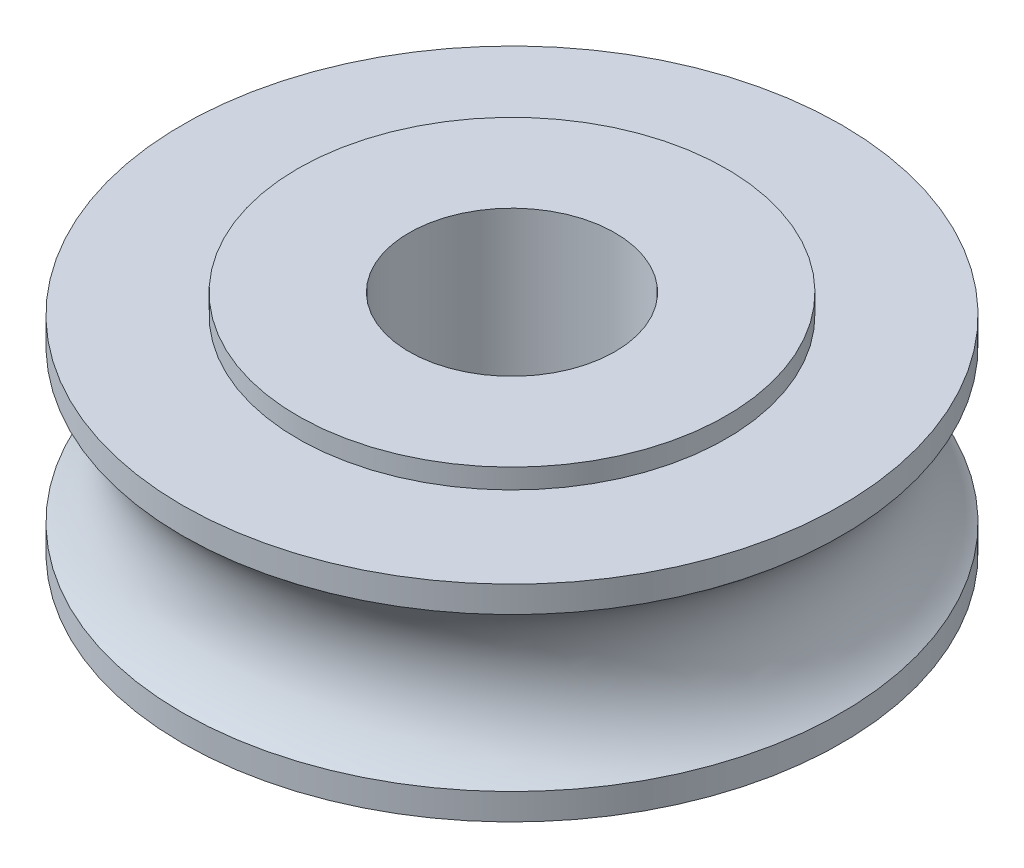
SolidWorks part; units mm, degrees
material "AISI 316 Annealed Stainless Steel Bar (SS)"
ref_plane "Front Plane" through (0, 0, 0) normal (0, 0, 1) x (1, 0, 0)
ref_plane "Top Plane" through (0, 0, 0) normal (0, 1, 0) x (1, 0, 0)
ref_plane "Right Plane" through (0, 0, 0) normal (1, 0, 0) x (0, 0, -1)
sketch "Sketch1" plane through (0, 0, 0) normal (0, 1, 0) x (1, 0, 0)
  circle A0 centre (0, 0) radius 12.7
extrude "Boss-Extrude1" add sketch "Sketch1" along normal blind 7.9375
sketch "Sketch2" plane through (0, 7.9375, 0) normal (0, 1, 0) x (1, 0, 0)
  circle A0 centre (0, 0) radius 3.9688
extrude "Cut-Extrude1" cut sketch "Sketch2" against normal through all
ref_axis "Axis1" through (0, 8.3344, 0) along (0, -1, 0)
sketch "Sketch4" plane through (0, 0, 0) normal (1, 0, 0) x (0, 0, -1)
  line L1 (-12.7, 7.9375) -> (-12.7, 0) construction
  line L3 (-12.7, 0) -> (12.7, 0) construction
  line L4 (-12.7, 6.9215) -> (-12.7, 1.016)
  arc A0 (-12.7, 6.9215) -> (-12.7, 1.016) centre (-14.9225, 3.9688) cw
  dimension "D1" = 1.016
  dimension "D2" = 1.016
revolve "Cut-Revolve1" cut sketch "Sketch4" angle 360 about axis through (0, 8.3344, 0) along (0, -1, 0)
ref_plane "Plane1" through (0, 3.937, 0) normal (0, -1, 0) x (-1, 0, 0)
sketch "Sketch5" plane through (0, 3.937, 0) normal (0, -1, 0) x (-1, 0, 0)
  circle A0 centre (0, 0) radius 3.9688 construction
  circle A1 centre (0, 0) radius 3.9688
  circle A2 centre (0, 0) radius 8.255
  dimension "D1" = 16.51
extrude "Boss-Extrude2" add sketch "Sketch5" along normal mid plane 9.525
